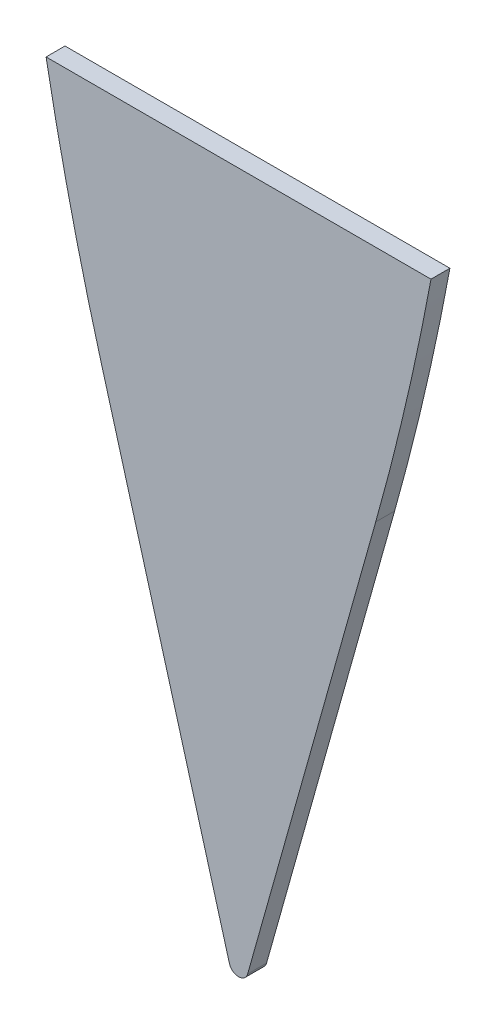
SolidWorks part; units mm, degrees
material "A-Glass Fiber"
ref_plane "Plan de face" through (0, 0, 0) normal (0, 0, 1) x (1, 0, 0)
ref_plane "Plan de dessus" through (0, 0, 0) normal (0, 1, 0) x (1, 0, 0)
ref_plane "Plan de droite" through (0, 0, 0) normal (1, 0, 0) x (0, 0, -1)
sketch "Sketch2" plane through (0, 0, 0) normal (0, 0, 1) x (1, 0, 0)
  line L0 (0, 0) -> (0, -350) construction
  line L1 (-75, 0) -> (75, 0)
  line L2 (125, -350) -> (-125, -350) construction
  line L3 (72.4663, -755.6809) -> (4.8134, -996.3531)
  line L5 (-72.4663, -755.6809) -> (-4.8134, -996.3531)
  arc A0 (75, 0) -> (72.4663, -755.6809) centre (-1287.9254, -373.2751) cw
  arc A1 (4.8134, -996.3531) -> (0, -1000) centre (0, -995) cw
  arc A2 (-75, 0) -> (-72.4663, -755.6809) centre (1287.9254, -373.2751) ccw
  arc A3 (0, -1000) -> (-4.8134, -996.3531) centre (0, -995) cw
  point P8 (0, -350)
  dimension "D3" = 5
  dimension "D1" = 350
  dimension "D2" = 250
  dimension "D4" = 250
extrude "Boss-Extrude1" add sketch "Sketch2" along normal blind 10
sketch "Sketch4" plane through (0, 0, 0) normal (0, 0, -1) x (-1, 0, 0)
  line L3 (-75, 0) -> (75, 0) construction
  line L8 (125.1917, -630) -> (-125.1917, -630)
  line L9 (-125.1917, -630) -> (-125.1917, 0)
  line L10 (-125.1917, 0) -> (125.1917, 0)
  line L11 (125.1917, 0) -> (125.1917, -630)
  arc A4 (72.4663, -755.6809) -> (75, 0) centre (-1287.9254, -373.2751) ccw construction
  arc A5 (-75, 0) -> (-72.4663, -755.6809) centre (1287.9254, -373.2751) ccw construction
  dimension "D4" = 630
extrude "Cut-Extrude2" cut sketch "Sketch4" against normal through all
